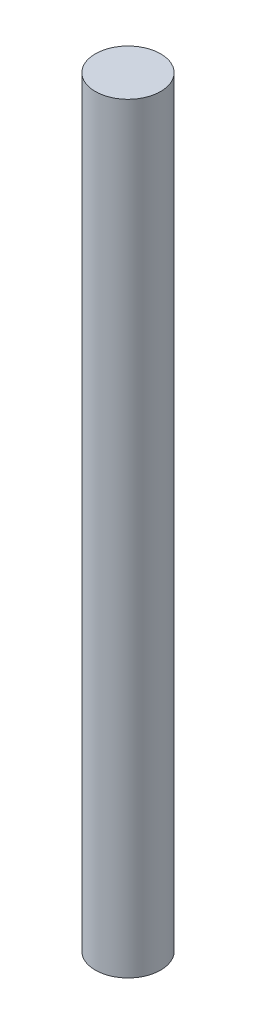
SolidWorks part; units mm, degrees
ref_plane "Front Plane" through (0, 0, 0) normal (0, 0, 1) x (1, 0, 0)
ref_plane "Top Plane" through (0, 0, 0) normal (0, 1, 0) x (1, 0, 0)
ref_plane "Right Plane" through (0, 0, 0) normal (1, 0, 0) x (0, 0, -1)
sketch "Sketch1" plane through (0, 0, 0) normal (0, 1, 0) x (1, 0, 0)
  circle A0 centre (0, 0) radius 1.5875
  dimension "D1" = 3.175
extrude "Boss-Extrude1" add sketch "Sketch1" along normal blind 37
sketch "Sketch2" plane through (0, 0, 0) normal (1, 0, 0) x (0, 0, -1)
  line L0 (0, 0) -> (0, 37) construction
  line L1 (-1.5875, 0) -> (1.5875, 0) construction
  line L2 (1.5875, 37) -> (-1.5875, 37) construction
  line L3 (0, 18.5) -> (1.5875, 18.5) construction
  line L4 (1.5875, 0) -> (1.5875, 37) construction
